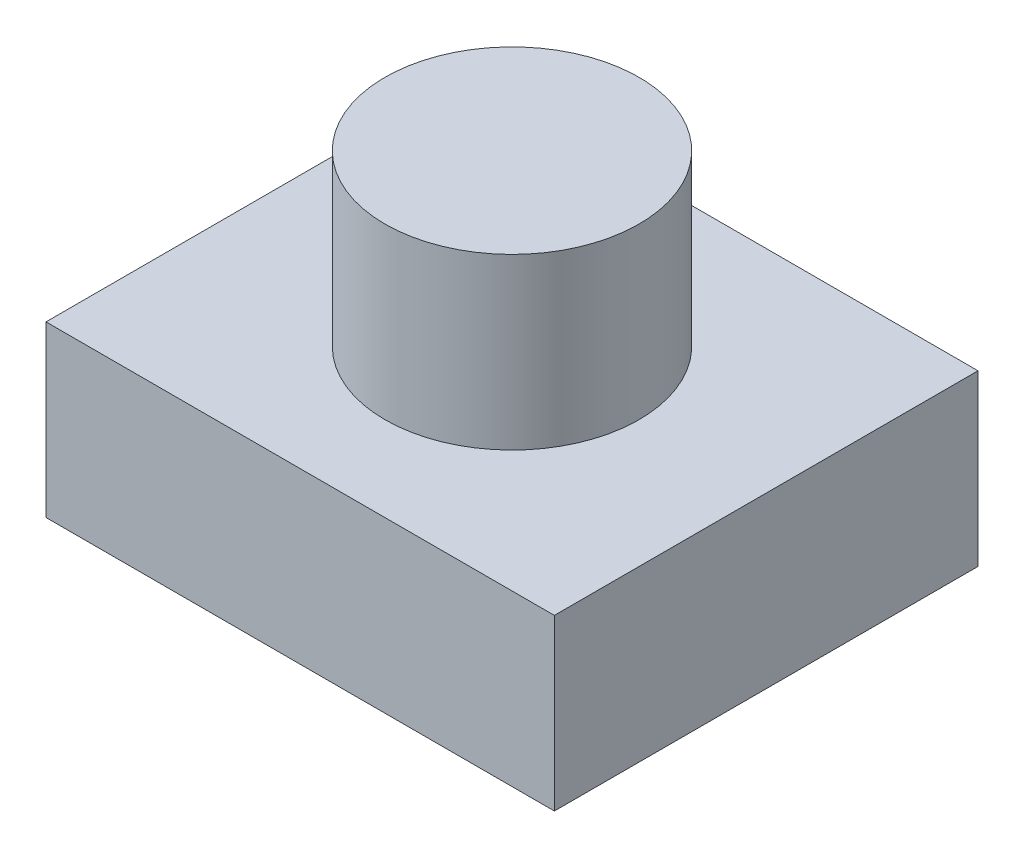
SolidWorks part; units mm, degrees
ref_plane "정면" through (0, 0, 0) normal (0, 0, 1) x (1, 0, 0)
ref_plane "윗면" through (0, 0, 0) normal (0, 1, 0) x (1, 0, 0)
ref_plane "우측면" through (0, 0, 0) normal (1, 0, 0) x (0, 0, -1)
sketch "스케치1" plane through (0, 0, 0) normal (0, 1, 0) x (1, 0, 0)
  line L1 (-50.5445, -13.2254) -> (9.4555, -13.2254)
  line L2 (-50.5445, -13.2254) -> (-50.5445, 36.7746)
  line L3 (-50.5445, 36.7746) -> (9.4555, 36.7746)
  line L4 (9.4555, -13.2254) -> (9.4555, 36.7746)
extrude "보스-돌출1" add sketch "스케치1" along normal blind 20
sketch "스케치3" plane through (0, 20, 0) normal (0, 1, 0) x (1, 0, 0)
  circle A0 centre (-20.5445, 11.7746) radius 15
  point P2 (-20.5445, 11.7746)
extrude "보스-돌출2" add sketch "스케치3" along normal blind 20
